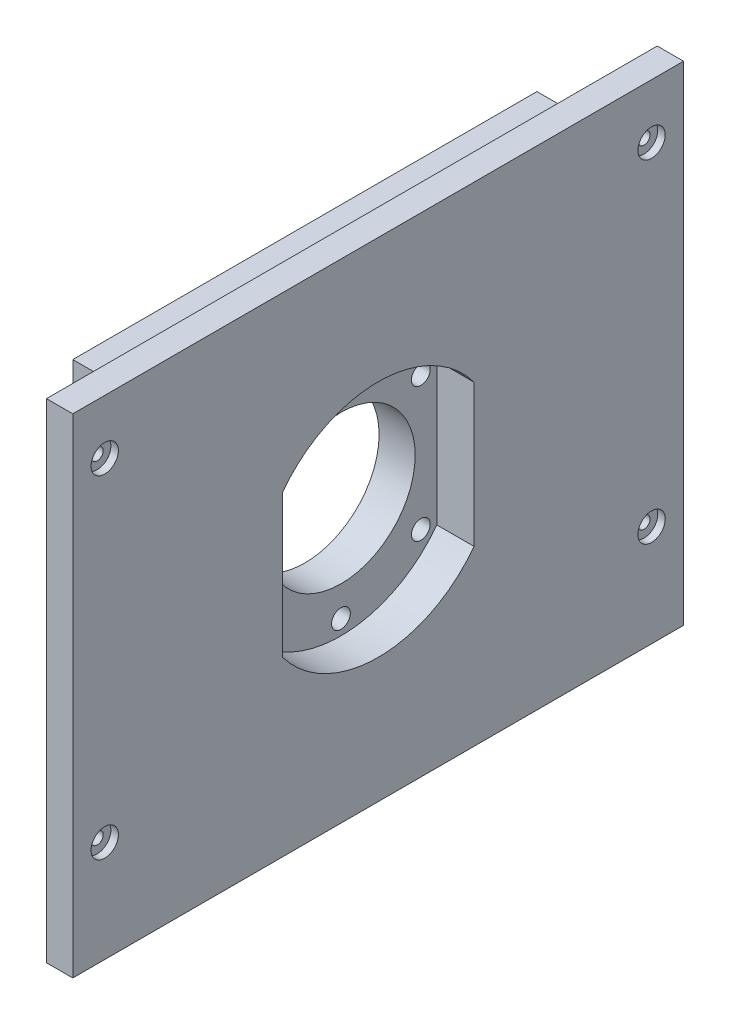
SolidWorks part; units mm, degrees
ref_plane "Front Plane" through (0, 0, 0) normal (0, 0, 1) x (1, 0, 0)
ref_plane "Top Plane" through (0, 0, 0) normal (0, 1, 0) x (1, 0, 0)
ref_plane "Right Plane" through (0, 0, 0) normal (1, 0, 0) x (0, 0, -1)
sketch "Sketch1" plane through (0, 0, 0) normal (1, 0, 0) x (0, 0, -1)
  line L1 (-150, 130) -> (175, 130)
  line L2 (-150, 130) -> (-150, -130)
  line L3 (-150, -130) -> (175, -130)
  line L4 (175, 130) -> (175, -130)
  point P4 (-150, 0)
  dimension "D1" = 260
  dimension "D2" = 150
  dimension "D3" = 175
extrude "Boss-Extrude1" add sketch "Sketch1" along normal blind 39
sketch "Sketch8" plane through (39, 0, 0) normal (1, 0, 0) x (0, 0, -1)
  circle A0 centre (158, 101) radius 6
  circle A1 centre (158, -76) radius 6
  circle A2 centre (-133, -76) radius 6
  circle A3 centre (-133, 101) radius 6
  dimension "D2" = 158
  dimension "D4" = 12
  dimension "D5" = 12
  dimension "D10" = 12
  dimension "D11" = 12
  dimension "D1" = 101
  dimension "D3" = 76
  dimension "D6" = 133
  dimension "D7" = 101
  dimension "D8" = 133
  dimension "D9" = 76
hole_wizard "CBORE for M6 Hex Head Bolt1" positions "Sketch11" profile "Sketch12" counterbore size "M6" standard "DIN"
sketch "Sketch11" plane through (39, 0, 0) normal (1, 0, 0) x (0, 0, -1)
  point P0 (158, 101)
  point P3 (158, -76)
  point P6 (-133, 101)
  point P9 (-133, -76)
sketch "Sketch12" plane through (39, 101, -158) normal (0, 1, 0) x (0, 0, -1)
  line L0 (0, 0) -> (0, 31.9228)
  line L1 (0, 31.9228) -> (3.2, 30)
  line L2 (3.2, 30) -> (3.2, 4)
  line L3 (3.2, 4) -> (7.2735, 4)
  line L4 (7.2735, 4) -> (7.2735, 0)
  line L5 (7.2735, 0) -> (0, 0)
  line L10 (0, 31.9228) -> (-3.2, 30) construction
  line L11 (0, -6.35) -> (0, 107.95) construction
  dimension "Hole Dia." = 6.4
  dimension "Hole Depth" = 30
  dimension "C'Bore Dia." = 14.547
  dimension "C'Bore Depth" = 4
  dimension "Drill Angle" = 118
ref_plane "Plane4" through (39, 0, 0) normal (1, 0, 0) x (0, 0, -1)
sketch "Sketch2" plane through (39, 0, 0) normal (1, 0, 0) x (0, 0, -1)
  line L0 (12.5, 0) -> (35.9553, 50.3001) construction
  line L1 (12.5, 0) -> (55.0155, -35.6747) construction
  line L2 (12.5, 0) -> (12.5, 55.5) construction
  line L3 (12.5, 0) -> (-10.9553, 50.3001) construction
  line L4 (12.5, 0) -> (12.5, -55.5) construction
  line L5 (12.5, 0) -> (-10.9553, -50.3001) construction
  line L6 (12.5, 0) -> (35.9553, -50.3001) construction
  line L7 (13.75, -55.5) -> (11.25, -55.5) construction
  line L8 (13.75, -60.75) -> (11.25, -60.75)
  line L9 (13.75, -50.25) -> (11.25, -50.25)
  line L10 (-30.819, -34.7172) -> (-29.212, -36.6323) construction
  line L11 (-34.8407, -38.0918) -> (-33.2337, -40.0069)
  line L12 (-26.7972, -31.3425) -> (-25.1902, -33.2576)
  line L13 (54.212, -36.6323) -> (55.819, -34.7172) construction
  line L14 (58.2337, -40.0069) -> (59.8407, -38.0918)
  line L15 (50.1902, -33.2576) -> (51.7972, -31.3425)
  line L16 (13.75, 55.5) -> (11.25, 55.5) construction
  line L17 (13.75, 50.25) -> (11.25, 50.25)
  line L18 (13.75, 60.75) -> (11.25, 60.75)
  line L19 (12.5, 0) -> (-61.0333, -61.7017) construction
  line L20 (54.212, 36.6323) -> (55.819, 34.7172) construction
  line L21 (50.1902, 33.2576) -> (51.7972, 31.3425)
  line L22 (58.2337, 40.0069) -> (59.8407, 38.0918)
  line L23 (-30.819, 34.7172) -> (-29.212, 36.6323) construction
  line L24 (-26.7972, 31.3425) -> (-25.1902, 33.2576)
  line L25 (-34.8407, 38.0918) -> (-33.2337, 40.0069)
  line L26 (175, -130) -> (175, 130) construction
  line L27 (-150, 130) -> (-150, -130) construction
  circle A0 centre (12.5, 0) radius 55.5 construction
  arc A1 (13.75, -60.75) -> (13.75, -50.25) centre (13.75, -55.5) ccw
  arc A2 (11.25, -50.25) -> (11.25, -60.75) centre (11.25, -55.5) ccw
  arc A3 (-34.8407, -38.0918) -> (-26.7972, -31.3425) centre (-30.819, -34.7172) cw
  arc A4 (-25.1902, -33.2576) -> (-33.2337, -40.0069) centre (-29.212, -36.6323) cw
  arc A5 (58.2337, -40.0069) -> (50.1902, -33.2576) centre (54.212, -36.6323) cw
  arc A6 (51.7972, -31.3425) -> (59.8407, -38.0918) centre (55.819, -34.7172) cw
  arc A7 (13.75, 50.25) -> (13.75, 60.75) centre (13.75, 55.5) ccw
  arc A8 (11.25, 60.75) -> (11.25, 50.25) centre (11.25, 55.5) ccw
  arc A9 (50.1902, 33.2576) -> (58.2337, 40.0069) centre (54.212, 36.6323) cw
  arc A10 (59.8407, 38.0918) -> (51.7972, 31.3425) centre (55.819, 34.7172) cw
  arc A11 (-26.7972, 31.3425) -> (-34.8407, 38.0918) centre (-30.819, 34.7172) cw
  arc A12 (-33.2337, 40.0069) -> (-25.1902, 33.2576) centre (-29.212, 36.6323) cw
  point P12 (12.5, -55.5)
  point P19 (-30.0155, -35.6747)
  point P24 (19, -55.5)
  point P25 (6, -55.5)
  point P28 (55.0155, -35.6747)
  point P35 (12.5, 55.5)
  point P40 (55.0155, 35.6747)
  point P47 (-30.0155, 35.6747)
  point P49 (19, 55.5)
  point P51 (6, 55.5)
  point P62 (-150, 0)
  dimension "D1" = 111
  dimension "D2" = 25
  dimension "D3" = 25
  dimension "D4" = 25
  dimension "D5" = 25
  dimension "D6" = 10.5
  dimension "D7" = 13
  dimension "D8" = 10.5
  dimension "D9" = 13
  dimension "D10" = 162.5
ref_plane "Plane1" through (39, 0, 0) normal (1, 0, 0) x (0, 0, -1)
sketch "Sketch3" plane through (39, 0, 0) normal (1, 0, 0) x (0, 0, -1)
  line L0 (175, 130) -> (-150, 130) construction
  line L1 (175, -130) -> (175, 130) construction
  circle A0 centre (12.5, 0) radius 39.51
  point P6 (12.5, 130)
  point P10 (175, 0)
  dimension "D1" = 79.02
extrude "Cut-Extrude2" cut sketch "Sketch3" against normal blind 39
sketch "Sketch5" plane through (39, 0, 0) normal (1, 0, 0) x (0, 0, -1)
  line L0 (12.5, 0) -> (12.5, -135.9451) construction
  line L1 (-38.5, 37.85) -> (-38.5, -37.85)
  line L2 (63.5, 37.85) -> (63.5, -37.85)
  line L3 (175, -130) -> (175, 130) construction
  line L4 (-150, 130) -> (-150, -130) construction
  arc A0 (-38.5, 37.85) -> (63.5, 37.85) centre (12.5, 0.0181) cw
  arc A1 (-38.5, -37.85) -> (63.5, -37.85) centre (12.5, -0.0181) ccw
  point P0 (12.5, 63.5181)
  point P7 (-38.5, 0)
  point P10 (63.5, 0)
  point P17 (-150, 0)
  dimension "D3" = 63.5
  dimension "D4" = 63.5
  dimension "D1" = 102
  dimension "D2" = 75.7
  dimension "D5" = 162.5
extrude "Cut-Extrude3" cut sketch "Sketch5" against normal blind 19.8
ref_plane "Plane2" through (0, 0, -175) normal (0, 0, -1) x (-1, 0, 0)
ref_plane "Plane3" through (0, -130, 0) normal (0, -1, 0) x (-1, 0, 0)
hole_wizard "Ø10.0mm Dowel Hole1" positions "Sketch16" profile "Sketch17" hole size "Ø10.0" standard "DIN"
sketch "Sketch16" plane through (39, 0, 0) normal (1, 0, 0) x (0, 0, -1)
  line L0 (54.212, -36.6323) -> (55.819, -34.7172) construction
  point P0 (12.5, 55.5)
  point P3 (55.0155, 35.6747)
  point P6 (-30.0155, 35.6747)
  point P9 (-30.0155, -35.6747)
  point P12 (12.5, -55.5)
  point P15 (55.0155, -35.6747)
sketch "Sketch17" plane through (39, 55.5, -12.5) normal (0, 1, 0) x (0, 0, -1)
  line L0 (0, 0) -> (0, 33.0043)
  line L1 (0, 33.0043) -> (5, 30)
  line L2 (5, 30) -> (5, 0)
  line L5 (5, 0) -> (0, 0)
  line L10 (0, 33.0043) -> (-5, 30) construction
  line L11 (0, -6.35) -> (0, 107.95) construction
  dimension "Hole Dia." = 10
  dimension "Hole Depth" = 30
  dimension "Drill Angle" = 118
sketch "Sketch18" plane through (0, 0, 0) normal (1, 0, 0) x (0, 0, -1)
  line L5 (175, 130) -> (-150, 130) construction
  line L10 (175, -130) -> (136, -130)
  line L11 (175, -130) -> (175, 130)
  line L12 (175, 130) -> (136, 130)
  line L13 (136, -130) -> (136, 130)
  line L14 (175, -130) -> (175, 130) construction
  line L15 (-150, -130) -> (-111, -130)
  line L16 (-150, -130) -> (-150, 130)
  line L17 (-150, 130) -> (-111, 130)
  line L18 (-111, -130) -> (-111, 130)
  line L19 (-150, 130) -> (-150, -130) construction
  line L20 (-150, -130) -> (175, -130) construction
  dimension "D1" = 39
  dimension "D2" = 39
extrude "Cut-Extrude5" cut sketch "Sketch18" along normal blind 25
sketch "Sketch19" plane through (0, -130, 0) normal (0, -1, 0) x (-1, 0, 0)
  line L1 (0, 136) -> (-25, 136)
  line L2 (0, 136) -> (0, -111)
  line L3 (0, -111) -> (-25, -111)
  line L4 (-25, 136) -> (-25, -111)
extrude "Cut-Extrude6" cut sketch "Sketch19" against normal blind 14
sketch "Sketch20" plane through (0, -130, 0) normal (0, -1, 0) x (-1, 0, 0)
  line L0 (0, -111) -> (0, 136) construction
  line L1 (0, 136) -> (-25, 136) construction
  line L2 (-25, -111) -> (0, -111) construction
  circle A0 centre (-14, 96.5) radius 3
  circle A1 centre (-14, -71.5) radius 3
  dimension "D1" = 14
  dimension "D2" = 39.5
  dimension "D4" = 6
  dimension "D5" = 6
  dimension "D3" = 39.5
hole_wizard "Ø6.0mm Dowel Hole1" positions "Sketch21" profile "Sketch22" hole size "Ø6.0" standard "ISO"
sketch "Sketch21" plane through (0, -116, 0) normal (0, -1, 0) x (-1, 0, 0)
  point P0 (-14, 96.5)
  point P3 (-14, -71.5)
sketch "Sketch22" plane through (14, -116, -96.5) normal (1, 0, 0) x (0, 0, -1)
  line L0 (0, 0) -> (0, 16.8026)
  line L1 (0, 16.8026) -> (3, 15)
  line L2 (3, 15) -> (3, 0)
  line L5 (3, 0) -> (0, 0)
  line L10 (0, 16.8026) -> (-3, 15) construction
  line L11 (0, -6.35) -> (0, 107.95) construction
  dimension "Hole Dia." = 6
  dimension "Hole Depth" = 15
  dimension "Drill Angle" = 118
sketch "Sketch23" plane through (0, 0, 0) normal (0, 0, 1) x (1, 0, 0)
  line L0 (0, 130) -> (0, -116) construction
  line L1 (25, 130) -> (0, 130)
  line L2 (25, 130) -> (25, 116)
  line L3 (25, 116) -> (0, 116)
  line L4 (0, 130) -> (0, 116)
  dimension "D1" = 14
extrude "Cut-Extrude7" cut sketch "Sketch23" against normal through all both and the other way through all
